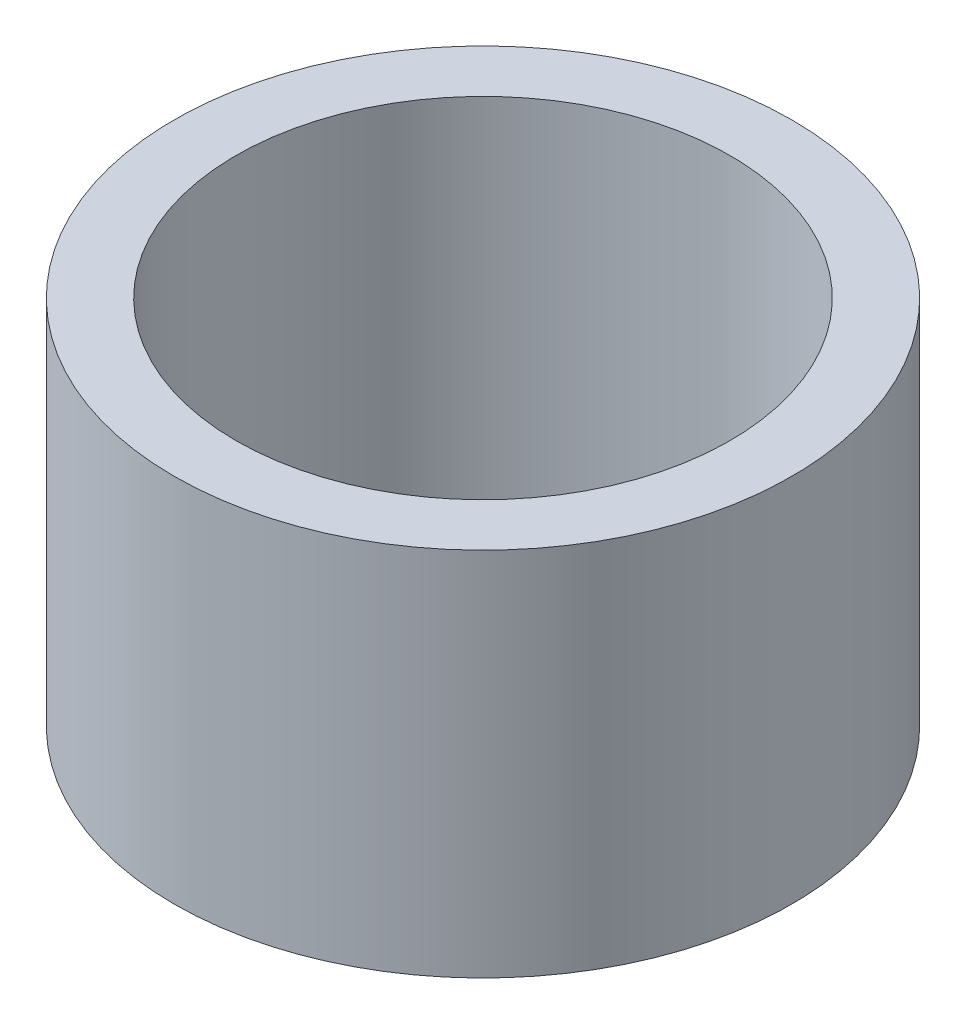
SolidWorks part; units mm, degrees
ref_plane "Alzado" through (0, 0, 0) normal (0, 0, 1) x (1, 0, 0)
ref_plane "Planta" through (0, 0, 0) normal (0, 1, 0) x (1, 0, 0)
ref_plane "Vista lateral" through (0, 0, 0) normal (1, 0, 0) x (0, 0, -1)
sketch "Croquis1" plane through (0, 0, 0) normal (0, 1, 0) x (1, 0, 0)
  circle A0 centre (0, 0) radius 4
  circle A1 centre (0, 0) radius 5
  dimension "D1" = 8
  dimension "D2" = 10
extrude "Saliente-Extruir1" add sketch "Croquis1" along normal blind 6
